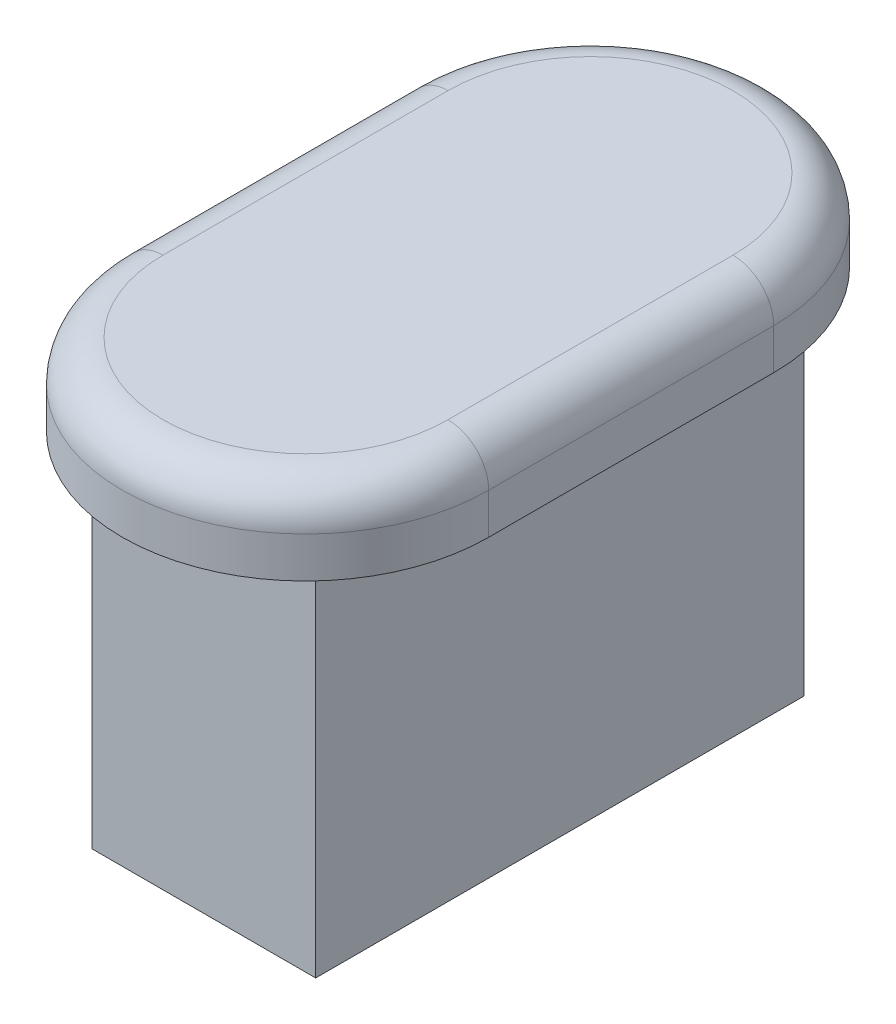
SolidWorks part; units mm, degrees
ref_plane "Спереди" through (0, 0, 0) normal (0, 0, 1) x (1, 0, 0)
ref_plane "Сверху" through (0, 0, 0) normal (0, 1, 0) x (1, 0, 0)
ref_plane "Справа" through (0, 0, 0) normal (1, 0, 0) x (0, 0, -1)
sketch "Эскиз1" plane through (0, 0, 0) normal (0, 1, 0) x (1, 0, 0)
  line L1 (-5.608, 5.9095) -> (-0.108, 5.9095)
  line L2 (-5.608, 5.9095) -> (-5.608, -6.0905)
  line L3 (-5.608, -6.0905) -> (-0.108, -6.0905)
  line L4 (-0.108, 5.9095) -> (-0.108, -6.0905)
  dimension "D1" = 12
  dimension "D2" = 5.5
extrude "Бобышка-Вытянуть1" add sketch "Эскиз1" along normal blind 9
sketch "Эскиз3" plane through (0, 9, 0) normal (0, 1, 0) x (1, 0, 0)
  line L0 (-2.858, 3.4095) -> (-2.858, -3.5905) construction
  line L1 (1.642, 3.4095) -> (1.642, -3.5905)
  line L2 (-7.358, 3.4095) -> (-7.358, -3.5905)
  line L3 (-5.608, 5.9095) -> (-5.608, -6.0905) construction
  line L4 (-0.108, -6.0905) -> (-0.108, 5.9095) construction
  line L5 (-7.358, -0.0905) -> (1.642, -0.0905) construction
  line L6 (-0.108, 5.9095) -> (-5.608, 5.9095) construction
  line L7 (-5.608, -6.0905) -> (-0.108, -6.0905) construction
  arc A0 (1.642, 3.4095) -> (-7.358, 3.4095) centre (-2.858, 3.4095) ccw
  arc A1 (-7.358, -3.5905) -> (1.642, -3.5905) centre (-2.858, -3.5905) ccw
  point P2 (-2.858, -0.0905)
  point P7 (-2.858, 7.9095)
  point P8 (-2.858, -8.0905)
  dimension "D1" = 16
  dimension "D2" = 9
  dimension "D3" = 2.75
  dimension "D4" = 2.75
  dimension "D5" = 6
  dimension "D6" = 6
extrude "Бобышка-Вытянуть2" add sketch "Эскиз3" along normal blind 2
fillet "Скругление1" radius 1 4 edges at (-2.858, 11, -7.9095) (1.642, 11, 0.0905) (-2.858, 11, 8.0905) (-7.358, 11, 0.0905)
